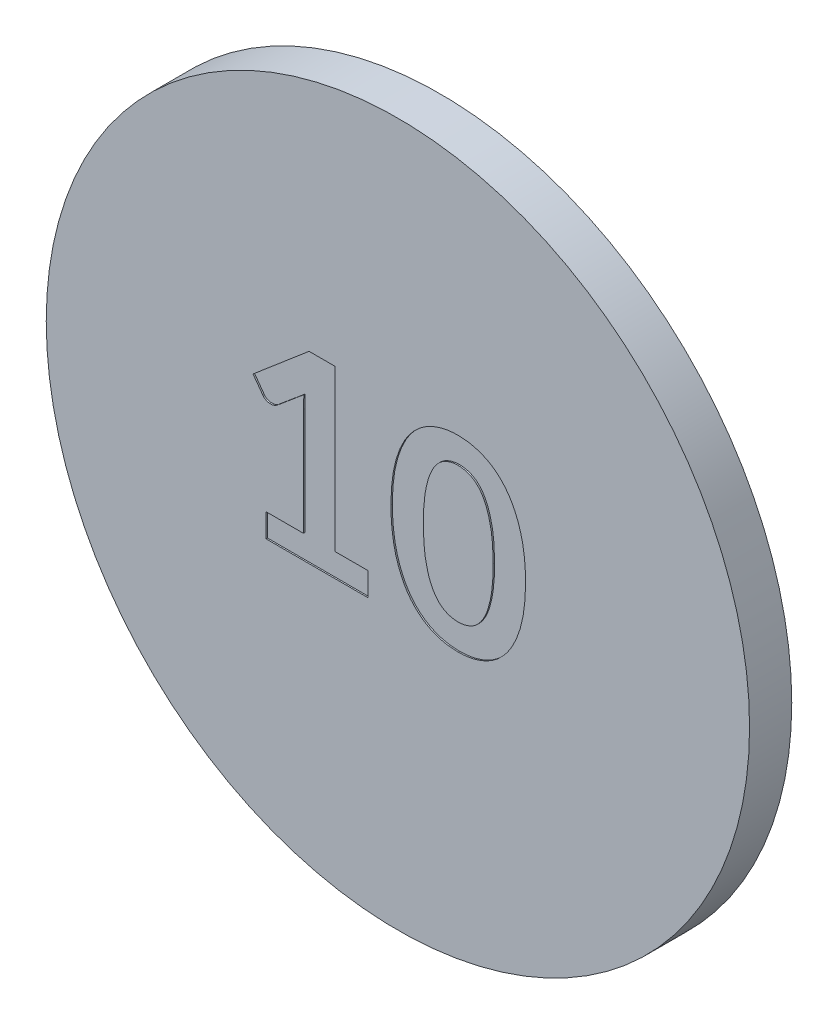
SolidWorks part; units mm, degrees
ref_plane "Front Plane" through (0, 0, 0) normal (1, 0, 0) x (0, 1, 0)
ref_plane "Top Plane" through (0, 0, 0) normal (0, 0, 1) x (0, 1, 0)
ref_plane "Right Plane" through (0, 0, 0) normal (0, 1, 0) x (-1, 0, 0)
sketch "Sketch1" plane through (0, 0, 0) normal (0, 0, 1) x (0, 1, 0)
  circle A0 centre (0, 0) radius 25
  dimension "D1" = 50
extrude "Boss-Extrude1" add sketch "Sketch1" along normal blind 3
sketch "Sketch3" plane through (0, 0, 3) normal (0, 0, 1) x (1, 0, 0)
  text T0 "10" font "Lato" height in points 48
extrude "Cut-Extrude1" cut sketch "Sketch3" against normal blind 0.1
